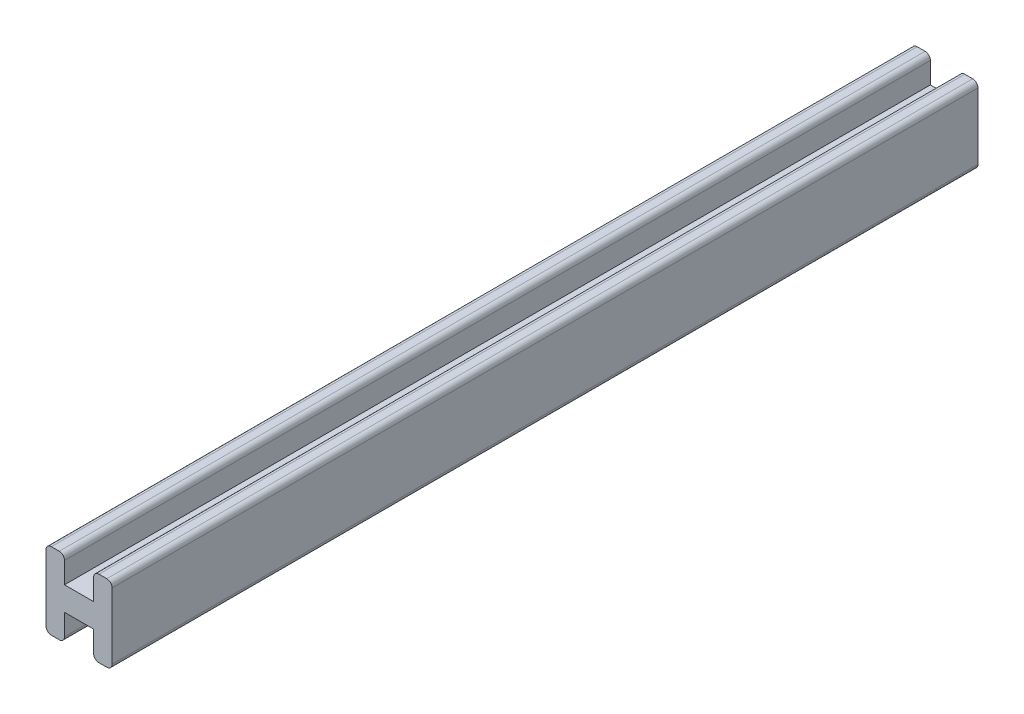
SolidWorks part; units mm, degrees
ref_plane "Front Plane" through (0, 0, 0) normal (0, 0, 1) x (1, 0, 0)
ref_plane "Top Plane" through (0, 0, 0) normal (0, 1, 0) x (1, 0, 0)
ref_plane "Right Plane" through (0, 0, 0) normal (1, 0, 0) x (0, 0, -1)
sketch "Sketch1" plane through (0, 0, 0) normal (0, 0, 1) x (1, 0, 0)
  line L0 (0, 0) -> (2, 0)
  line L1 (55, 0) -> (-55, 0) construction
  line L2 (2, 0) -> (2, 2)
  line L3 (2, 2) -> (3.5, 2)
  line L4 (3.5, 2) -> (3.5, -4)
  line L5 (3.5, -4) -> (2, -4)
  line L6 (2, -4) -> (2, -2)
  line L7 (2, -2) -> (0, -2)
  line L8 (0, -55) -> (0, 55) construction
  line L9 (0, -2) -> (0, -4)
  line L10 (0, -4) -> (-1.5, -4)
  line L11 (-1.5, -4) -> (-1.5, 2)
  line L12 (-1.5, 2) -> (0, 2)
  line L13 (0, 2) -> (0, 0)
extrude "Boss-Extrude1" add sketch "Sketch1" along normal blind 21
sketch "Sketch2" plane through (0, 0, 21) normal (0, 0, 1) x (1, 0, 0)
  line L0 (-1.5, 2) -> (-1.5, 1.9)
  line L1 (-1.5, 2) -> (-1.5, -4) construction
  line L2 (-1.5, 1.9) -> (-0.1, 1.9)
  line L3 (-0.1, 1.9) -> (-0.1, -0.1)
  line L4 (-0.1, -0.1) -> (2.1, -0.1)
  line L5 (1, -0.1) -> (1, 49999.9) construction
  line L6 (2.1, 1.9) -> (2.1, -0.1)
  line L7 (3.5, 1.9) -> (2.1, 1.9)
  line L8 (3.5, 2) -> (3.5, 1.9)
  line L9 (-1.5, 2) -> (3.5, 2)
  line L10 (-1.5, -1) -> (49998.5, -1) construction
  line L11 (-1.5, -4) -> (3.5, -4)
  line L12 (3.5, -4) -> (3.5, -3.9)
  line L13 (3.5, -3.9) -> (2.1, -3.9)
  line L14 (2.1, -3.9) -> (2.1, -1.9)
  line L15 (-0.1, -1.9) -> (2.1, -1.9)
  line L16 (-0.1, -3.9) -> (-0.1, -1.9)
  line L17 (-1.5, -3.9) -> (-0.1, -3.9)
  line L18 (-1.5, -4) -> (-1.5, -3.9)
  point P11 (1, -0.1)
  point P16 (-1.5, -1)
  point P25 (1, -1.9)
extrude "Cut-Extrude1" cut sketch "Sketch2" against normal through all
sketch "Sketch3" plane through (0, 0, 0) normal (0, 0, -1) x (-1, 0, 0)
  line L24 (-2.1, -0.1) -> (-2.1, 1.9)
  line L25 (-2.1, 1.9) -> (-3.5, 1.9)
  line L26 (-3.5, 1.9) -> (-3.5, -3.9)
  line L27 (-3.5, -3.9) -> (-2.1, -3.9)
  line L28 (-2.1, -3.9) -> (-2.1, -1.9)
  line L29 (-2.1, -1.9) -> (0.1, -1.9)
  line L30 (0.1, -1.9) -> (0.1, -3.9)
  line L31 (0.1, -3.9) -> (1.5, -3.9)
  line L32 (1.5, -3.9) -> (1.5, 1.9)
  line L33 (1.5, 1.9) -> (0.1, 1.9)
  line L34 (0.1, 1.9) -> (0.1, -0.1)
  line L35 (0.1, -0.1) -> (-2.1, -0.1)
  line L36 (-2.1, -0.1) -> (-2.1, 1.9)
  line L37 (-2.1, 1.9) -> (-3.5, 1.9)
  line L38 (-3.5, 1.9) -> (-3.5, -3.9)
  line L39 (-3.5, -3.9) -> (-2.1, -3.9)
  line L40 (-2.1, -3.9) -> (-2.1, -1.9)
  line L41 (-2.1, -1.9) -> (0.1, -1.9)
  line L42 (0.1, -1.9) -> (0.1, -3.9)
  line L43 (0.1, -3.9) -> (1.5, -3.9)
  line L44 (1.5, -3.9) -> (1.5, 1.9)
  line L45 (1.5, 1.9) -> (0.1, 1.9)
  line L46 (0.1, 1.9) -> (0.1, -0.1)
  line L47 (0.1, -0.1) -> (-2.1, -0.1)
  dimension "D1" = 0
extrude "Boss-Extrude2" add sketch "Sketch3" along normal blind 49
fillet "Fillet1" radius 0.4 8 edges at (-1.5, 1.9, -14) (-0.1, 1.9, -14) (-1.5, -3.9, -14) (-0.1, -3.9, -14) (2.1, -3.9, -14) (3.5, -3.9, -14) (3.5, 1.9, -14) (2.1, 1.9, -14)
sketch "Sketch4" plane through (0, 0, 21) normal (0, 0, 1) x (1, 0, 0)
  line L1 (-2.3353, 2.4707) -> (5.055, 2.4707)
  line L2 (-2.3353, 2.4707) -> (-2.3353, -4.4549)
  line L3 (-2.3353, -4.4549) -> (5.055, -4.4549)
  line L4 (5.055, 2.4707) -> (5.055, -4.4549)
extrude "Cut-Extrude2" cut sketch "Sketch4" against normal blind 4.5
